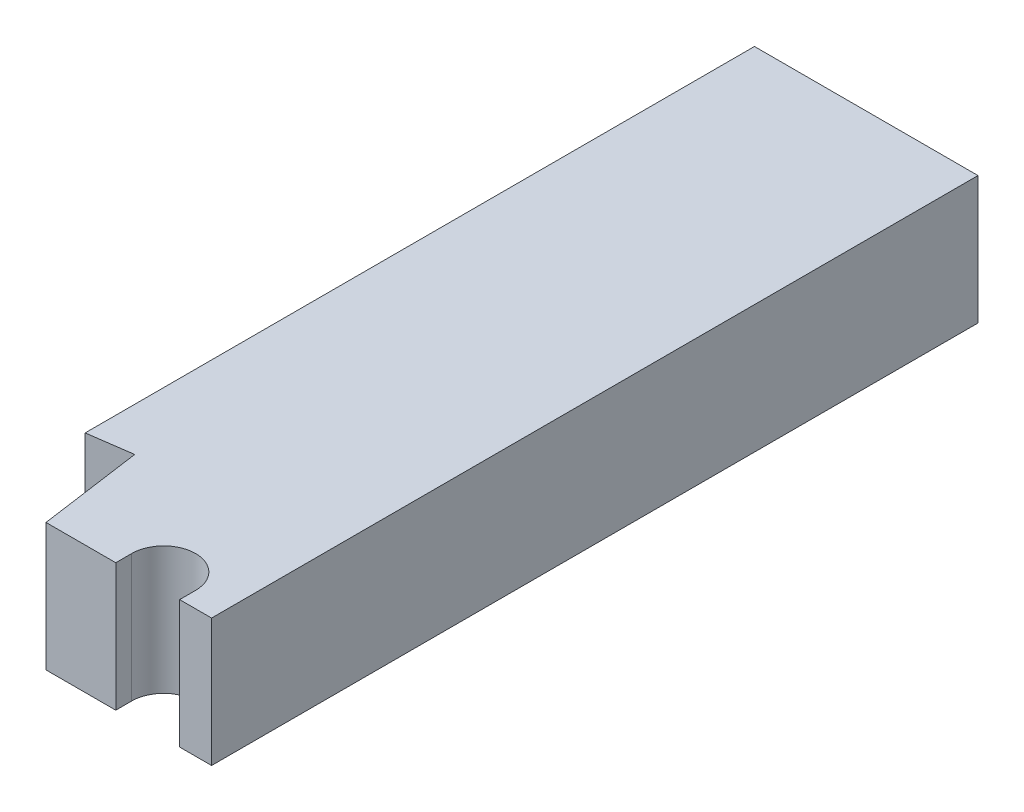
SolidWorks part; units mm, degrees
material "Pine"
ref_plane "X-Y Datum" through (0, 0, 0) normal (0, 0, 1) x (1, 0, 0)
ref_plane "X-Z Datum" through (0, 0, 0) normal (0, 1, 0) x (1, 0, 0)
ref_plane "Y-Z Datum" through (0, 0, 0) normal (1, 0, 0) x (0, 0, -1)
sketch "Sketch1" plane through (0, 0, 0) normal (0, 0, 1) x (1, 0, 0)
  line L1 (-50.8, 25.4) -> (50.8, 25.4)
  line L2 (-50.8, 25.4) -> (-50.8, -25.4)
  line L3 (-50.8, -25.4) -> (50.8, -25.4)
  line L4 (50.8, 25.4) -> (50.8, -25.4)
  line L5 (-50.8, 25.4) -> (50.8, -25.4) construction
  line L6 (-50.8, -25.4) -> (50.8, 25.4) construction
  point P0 (0, 0)
  dimension "D1" = 101.6
  dimension "D2" = 50.8
extrude "Boss-Extrude1" add sketch "Sketch1" along normal blind 304.8
sketch "Sketch2" plane through (0, 25.4, 0) normal (0, 1, 0) x (1, 0, 0)
  line L0 (50.8, -304.8) -> (50.8, 0) construction
  line L1 (-50.8, -279.0039) -> (-31.75, -276.3266) construction
  line L2 (50.8, -304.8) -> (-50.8, -304.8) construction
  line L3 (25.4, -298.45) -> (25.4, -304.8)
  line L4 (25.4, -304.8) -> (23.6985, -304.8)
  line L5 (0, -298.45) -> (0, -304.8)
  line L6 (0, -304.8) -> (1.7015, -304.8)
  line L7 (-31.75, -276.3266) -> (-27.7483, -304.8)
  line L8 (-50.8, -304.8) -> (-50.8, 0) construction
  line L9 (-50.8, -304.8) -> (50.8, -304.8) construction
  line L10 (-50.8, -279.0039) -> (-50.8, -304.8)
  line L11 (-50.8, -304.8) -> (-27.7483, -304.8)
  line L12 (-31.75, -276.3266) -> (-33.5175, -263.7502)
  line L13 (-33.5175, -263.7502) -> (-50.8, -266.1791)
  line L14 (-50.8, -304.8) -> (-50.8, 0) construction
  line L15 (-50.8, -266.1791) -> (-50.8, -279.0039)
  circle A0 centre (12.7, -298.45) radius 12.7
  line M2 (-50.8, 0) -> (-50.8, -304.8)
  line M3 (-50.8, -304.8) -> (50.8, -304.8)
  dimension "D2" = 25.4
  dimension "D1" = 38.1
  dimension "D3" = 6.35
  dimension "D4" = 8
  dimension "D5" = 28.4734
  dimension "D6" = 19.05
  dimension "D7" = 12.7
extrude "Cut-Extrude1" cut sketch "Sketch2" against normal through all both and the other way through all contours A0 M3 | A0 L3 M3 | A0 L5 M3 | L7 L1 M2 M3 | L1 L12 L13 M2
sketch "Sketch3" plane through (0, 25.4, 0) normal (0, 1, 0) x (1, 0, 0)
  line L0 (50.8, -304.8) -> (25.4, -304.8) construction
  line L1 (50.8, 0) -> (38.1, 0)
  line L2 (50.8, 0) -> (50.8, -304.8)
  line L3 (50.8, -304.8) -> (38.1, -304.8)
  line L4 (38.1, 0) -> (38.1, -304.8)
  line L5 (-50.8, -266.1791) -> (-50.8, 0) construction
  dimension "D1" = 88.9
extrude "Cut-Extrude2" cut sketch "Sketch3" against normal through all both
